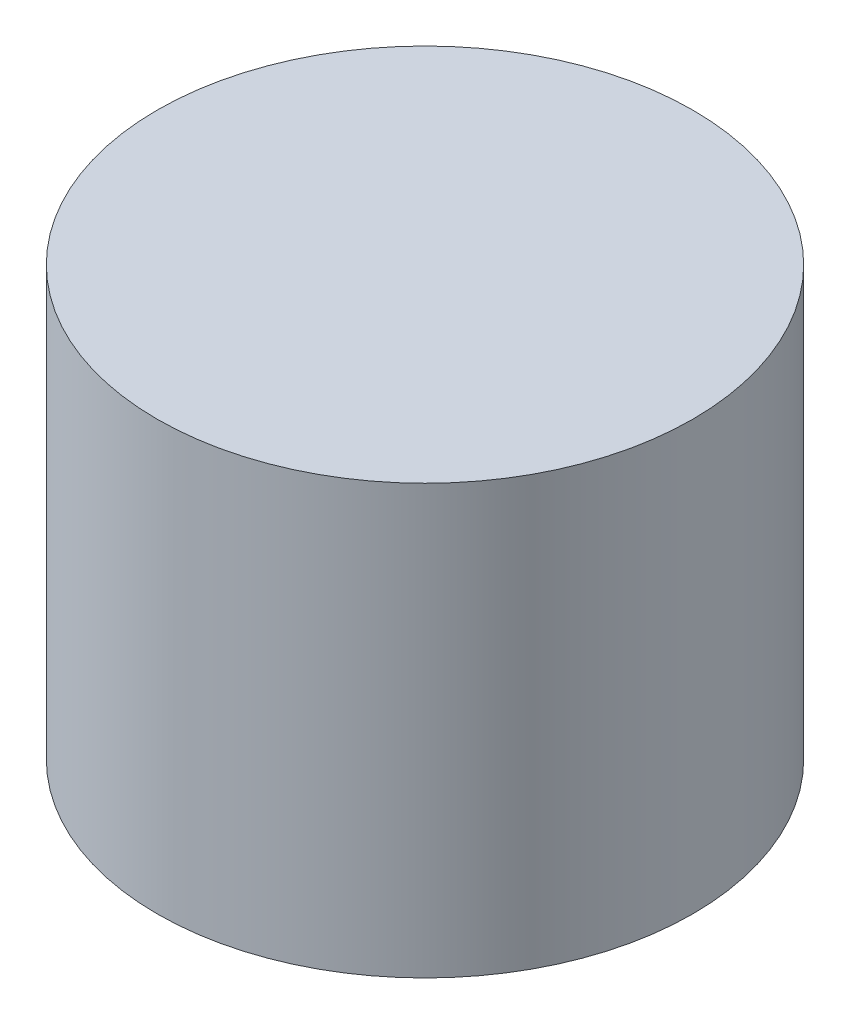
SolidWorks part; units mm, degrees
material "Nickel"
ref_plane "Front Plane" through (0, 0, 0) normal (0, 0, 1) x (1, 0, 0)
ref_plane "Top Plane" through (0, 0, 0) normal (0, 1, 0) x (1, 0, 0)
ref_plane "Right Plane" through (0, 0, 0) normal (1, 0, 0) x (0, 0, -1)
sketch "Sketch1" plane through (0, 0, 0) normal (0, 1, 0) x (1, 0, 0)
  circle A0 centre (0, 0) radius 3.9688
  dimension "D1" = 7.9375
extrude "Boss-Extrude1" add sketch "Sketch1" along normal blind 6.35
